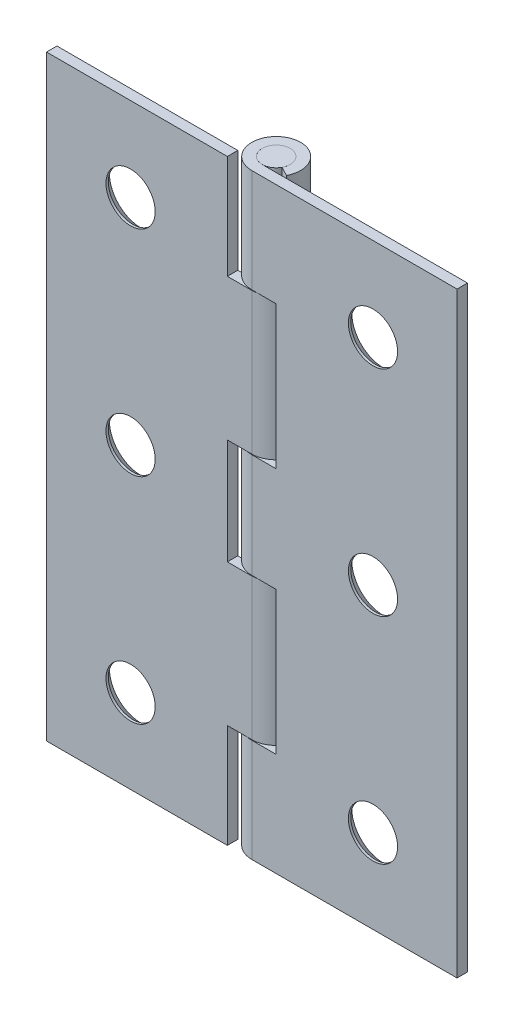
SolidWorks part; units mm, degrees
ref_plane "Front" through (0, 0, 0) normal (0, 0, 1) x (1, 0, 0)
ref_plane "Top" through (0, 0, 0) normal (0, 1, 0) x (1, 0, 0)
ref_plane "Right" through (0, 0, 0) normal (1, 0, 0) x (0, 0, -1)
sketch "Sketch1" plane through (0, 0, 0) normal (0, 1, 0) x (1, 0, 0)
  line L0 (0, -1.1906) -> (17.4752, -1.1906)
  line L1 (17.4752, -1.1906) -> (17.4752, -2.0796)
  line L2 (17.4752, -2.0796) -> (0, -2.0796)
  line L3 (1.8404, -0.9684) -> (1.0537, -0.5544)
  line L4 (1.0537, -0.5544) -> (0, 0) construction
  line L5 (1.8404, -0.9684) -> (1.7235, -1.1906) construction
  arc A0 (1.0537, -0.5544) -> (0, -1.1906) centre (0, 0) ccw
  arc A1 (1.8404, -0.9684) -> (0, -2.0796) centre (0, 0) ccw
  dimension "B Half Width" = 17.4752
  dimension "D1" = 0.2223
extrude "Extrude1" add sketch "Sketch1" along normal mid plane 50.8
ref_plane "Plane2" through (10.3187, 0, 0) normal (1, 0, 0) x (0, 0, -1)
sketch "Sketch7" plane through (10.3187, 0, 0) normal (1, 0, 0) x (0, 0, -1)
  line L0 (1.8223, 18.2562) -> (-3.6624, 18.2562) construction
  line L1 (-1.1906, 18.2562) -> (-1.1906, 20.9487)
  line L2 (-1.1906, 20.9487) -> (-1.8773, 20.3517)
  line L3 (-1.8773, 20.3517) -> (-2.0796, 20.3517)
  line L4 (-2.0796, 20.3517) -> (-2.0796, 18.2562)
  line L5 (-2.0796, 18.2562) -> (-1.1906, 18.2562)
  line L6 (-1.1906, 15.5638) -> (-1.8773, 16.1607) construction
  line L7 (-1.1906, 25.4) -> (-1.1906, -25.4) construction
  line L9 (-2.0796, 25.4) -> (-1.1906, 25.4) construction
  line L10 (-2.0796, 25.4) -> (-2.0796, -25.4) construction
  dimension "D1" = 82
  dimension "Screw Head Dia" = 5.3848
  dimension "X Thru Dia" = 4.191
  dimension "G" = 7.1437
revolve "Cut-Revolve1" cut sketch "Sketch7" angle 360 about L0
pattern_linear "LPattern2" count 3 spacing 18.2562 along (0, -1, 0) of "Cut-Revolve1"
mirror "Mirror2" about plane through (0, 0, 0) normal (1, 0, 0) of bodies 114 108
sketch "Sketch4" plane through (0, 0, 0) normal (0, 0, 1) x (1, 0, 0)
  line L0 (-2.0796, 25.4) -> (-2.0796, 16.6116) construction
  line L1 (-2.0796, 16.6116) -> (2.0796, 16.6116)
  line L2 (2.0796, 16.6116) -> (2.0796, 4.445)
  line L3 (2.0796, 4.445) -> (-2.0796, 4.445)
  line L4 (-2.0796, 4.445) -> (-2.0796, -4.445) construction
  line L5 (-2.0796, -4.445) -> (2.0796, -4.445)
  line L6 (2.0796, -4.445) -> (2.0796, -16.6116)
  line L7 (2.0796, -16.6116) -> (-2.0796, -16.6116)
  line L8 (-2.0796, -16.6116) -> (-2.0796, -25.4) construction
  line L9 (17.4752, -25.4) -> (0, -25.4) construction
  line L10 (17.4752, 25.4) -> (0, 25.4) construction
  line L11 (-2.0796, 25.4) -> (-2.0796, -25.4) construction
  line L12 (2.0796, -25.4) -> (2.0796, 25.4) construction
  line L13 (-2.0796, -16.6116) -> (-2.0796, -4.445)
  line L14 (-2.0796, 4.445) -> (-2.0796, 16.6116)
  dimension "D" = 8.89
  dimension "C" = 33.2232
extrude "Cut-Extrude1" cut sketch "Sketch4" against normal through all and the other way through all
sketch "Sketch5" plane through (0, 0, 0) normal (0, 0, 1) x (1, 0, 0)
  line L0 (2.0796, -4.445) -> (2.0796, -16.6116) construction
  line L1 (-2.0796, -25.4) -> (2.0796, -25.4)
  line L2 (-2.0796, -25.4) -> (-2.0796, -16.5608)
  line L3 (-2.0796, -16.5608) -> (2.0796, -16.5608)
  line L4 (2.0796, -25.4) -> (2.0796, -16.5608)
  line L5 (-2.0796, -16.6116) -> (-2.0796, -4.445) construction
  line L6 (-2.0796, -4.4958) -> (2.0796, -4.4958)
  line L7 (-2.0796, -4.4958) -> (-2.0796, 4.4958)
  line L8 (-2.0796, 4.4958) -> (2.0796, 4.4958)
  line L9 (2.0796, -4.4958) -> (2.0796, 4.4958)
  line L10 (2.0796, 16.6116) -> (2.0796, 4.445) construction
  line L11 (-2.0796, 16.6116) -> (2.0796, 16.6116) construction
  line L12 (-2.0796, 25.4) -> (2.0796, 25.4)
  line L13 (-2.0796, 25.4) -> (-2.0796, 16.5608)
  line L14 (-2.0796, 16.5608) -> (2.0796, 16.5608)
  line L15 (2.0796, 25.4) -> (2.0796, 16.5608)
  line L16 (2.0796, 4.445) -> (-2.0796, 4.445) construction
  line L17 (-2.0796, -4.445) -> (2.0796, -4.445) construction
  line L18 (2.0796, -16.6116) -> (-2.0796, -16.6116) construction
  dimension "D1" = 0.0508
  dimension "D2" = 0.0508
  dimension "D3" = 0.0508
  dimension "D4" = 0.0508
extrude "Cut-Extrude2" cut sketch "Sketch5" against normal through all and the other way through all
sketch "Sketch6" plane through (0, 0, 0) normal (0, 1, 0) x (1, 0, 0)
  line L0 (0, 0) -> (0, 1.1881) construction
  line L1 (0, 1.1881) -> (0, 1.1906) construction
  circle A0 centre (0, 0) radius 1.1881
  arc A1 (1.0537, -0.5544) -> (0, -1.1906) centre (0, 0) ccw construction
  dimension "D1" = 0.0025
extrude "Extrude2" add sketch "Sketch6" against normal up to surface and the other way up to surface
equation "\"D1@Sketch1\"=\"M Mat'l Thickness@Sketch1\"/4"
